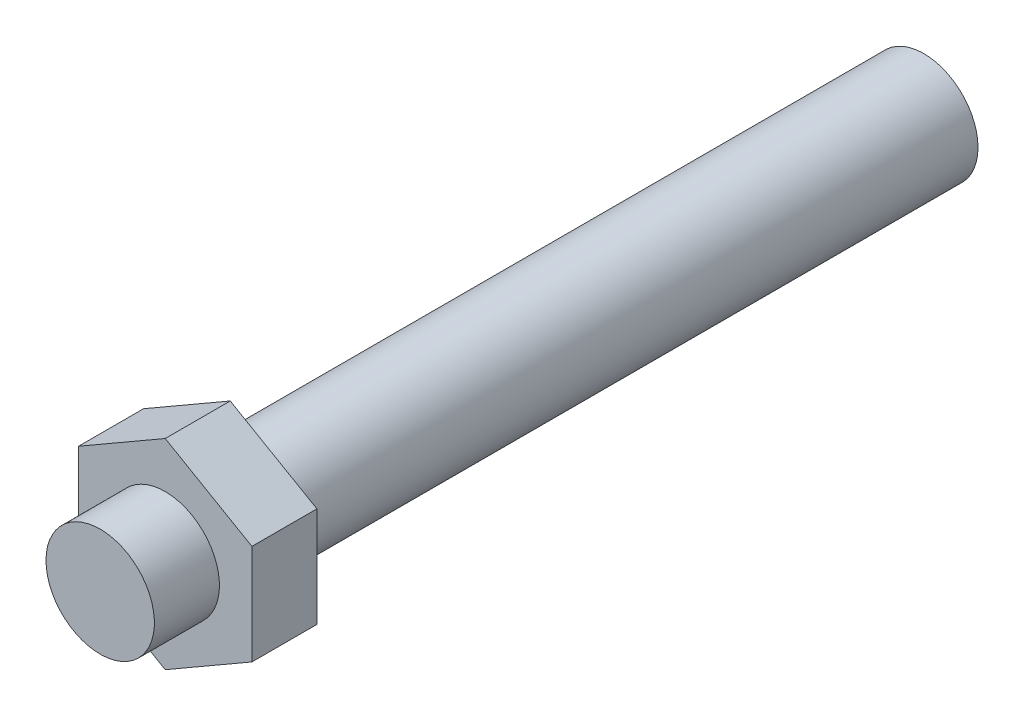
SolidWorks part; units mm, degrees
ref_plane "Plane1" through (0, 0, 0) normal (0, 0, 1) x (1, 0, 0)
ref_plane "Plane2" through (0, 0, 0) normal (0, 1, 0) x (1, 0, 0)
ref_plane "Plane3" through (0, 0, 0) normal (1, 0, 0) x (0, 0, -1)
sketch "Sketch1" plane through (0, 0, 0) normal (0, 0, 1) x (1, 0, 0)
  circle A0 centre (0, 0) radius 7.9375
  dimension "D1" = 15.875
extrude "Base-Extrude" add sketch "Sketch1" along normal blind 101.6
sketch "Sketch2" plane through (0, 0, 101.6) normal (0, 0, 1) x (1, 0, 0)
  line L1 (12.7, -7.3323) -> (12.7, 7.3323)
  line L2 (12.7, 7.3323) -> (0, 14.6647)
  line L3 (0, 14.6647) -> (-12.7, 7.3323)
  line L4 (-12.7, 7.3323) -> (-12.7, -7.3323)
  line L5 (-12.7, -7.3323) -> (0, -14.6647)
  line L6 (0, -14.6647) -> (12.7, -7.3323)
  circle A0 centre (0, 0) radius 12.7 construction
  dimension "D1" = 25.4
extrude "Boss-Extrude1" add sketch "Sketch2" along normal blind 9.525
sketch "Sketch3" plane through (0, 0, 111.125) normal (0, 0, 1) x (1, 0, 0)
  circle A0 centre (0, 0) radius 7.9375
  dimension "D1" = 15.875
extrude "Boss-Extrude2" add sketch "Sketch3" along normal blind 9.525
